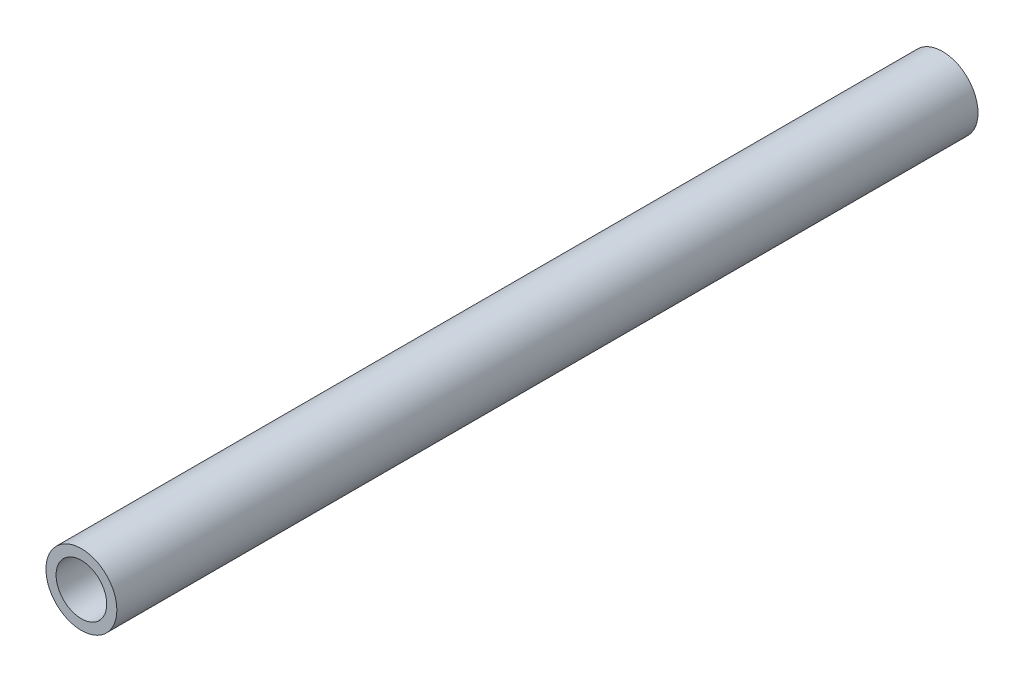
SolidWorks part; units mm, degrees
material "1.0553 (S355J0)"
ref_plane "Front Plane" through (0, 0, 0) normal (0, 0, 1) x (1, 0, 0)
ref_plane "Top Plane" through (0, 0, 0) normal (0, 1, 0) x (1, 0, 0)
ref_plane "Right Plane" through (0, 0, 0) normal (1, 0, 0) x (0, 0, -1)
other "Center of Mass"
sketch "Sketch1" plane through (0, 0, 0) normal (0, 0, 1) x (1, 0, 0)
  circle A0 centre (0, 0) radius 70
  circle A1 centre (0, 0) radius 50
  dimension "D1" = 140
  dimension "D2" = 20
extrude "Boss-Extrude1" add sketch "Sketch1" along normal mid plane 1700
